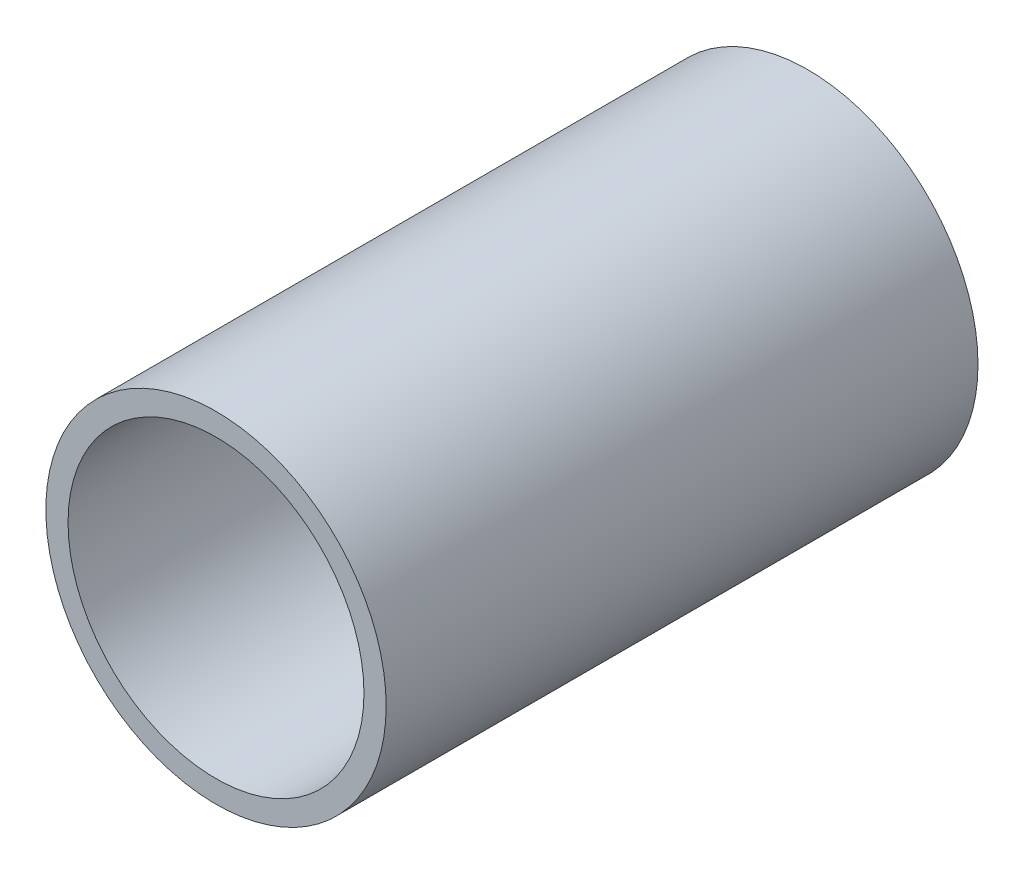
SolidWorks part; units mm, degrees
ref_plane "Front Plane" through (0, 0, 0) normal (0, 0, 1) x (1, 0, 0)
ref_plane "Top Plane" through (0, 0, 0) normal (0, 1, 0) x (1, 0, 0)
ref_plane "Right Plane" through (0, 0, 0) normal (1, 0, 0) x (0, 0, -1)
sketch "Sketch1" plane through (0, 0, 0) normal (0, 0, 1) x (1, 0, 0)
  circle A0 centre (0, 0) radius 15
  circle A1 centre (0, 0) radius 17.25
  dimension "D1" = 30
  dimension "D2" = 2.25
extrude "Boss-Extrude1" add sketch "Sketch1" along normal blind 60
